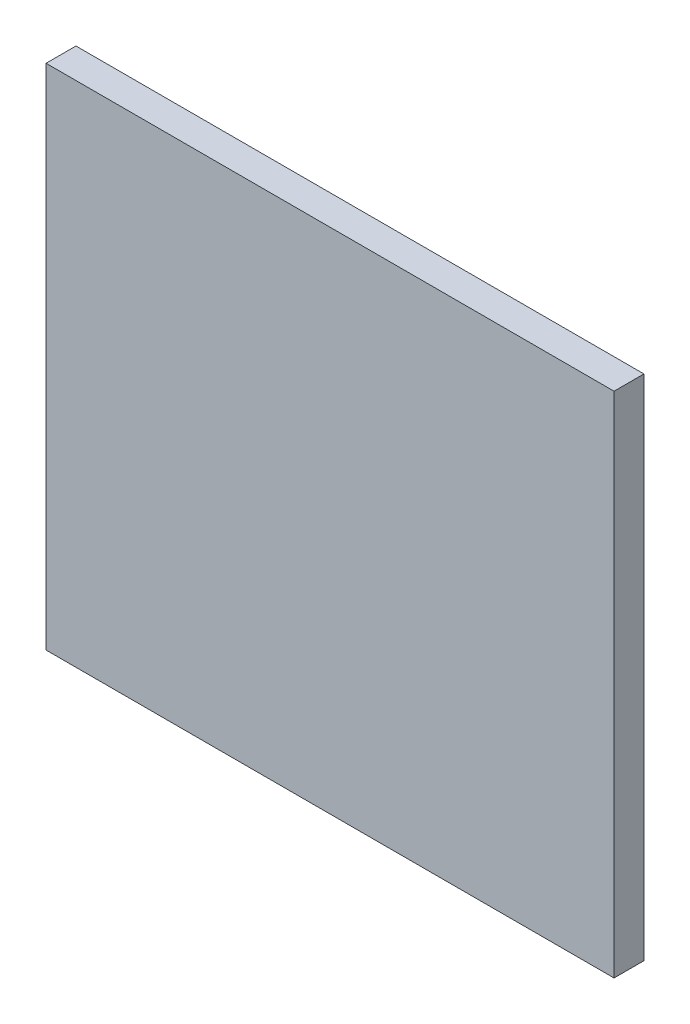
SolidWorks part; units mm, degrees
ref_plane "Ön Düzlem" through (0, 0, 0) normal (0, 0, 1) x (1, 0, 0)
ref_plane "Üst Düzlem" through (0, 0, 0) normal (0, 1, 0) x (1, 0, 0)
ref_plane "Sağ Düzlem" through (0, 0, 0) normal (1, 0, 0) x (0, 0, -1)
sketch "Sketch1" plane through (0, 0, 0) normal (0, 0, 1) x (1, 0, 0)
  line L1 (-95, -85) -> (95, -85)
  line L2 (-95, -85) -> (-95, 85)
  line L3 (-95, 85) -> (95, 85)
  line L4 (95, -85) -> (95, 85)
  line L5 (-95, -85) -> (95, 85) construction
  line L6 (-95, 85) -> (95, -85) construction
  point P0 (0, 0)
  dimension "D1" = 190
  dimension "D2" = 170
extrude "Boss-Extrude1" add sketch "Sketch1" along normal blind 10
